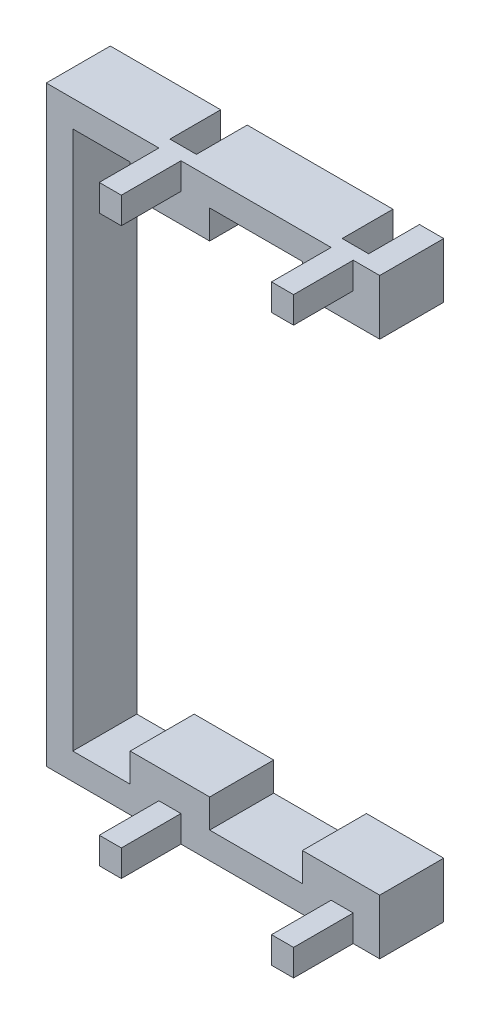
SolidWorks part; units mm, degrees
ref_plane "Front Plane" through (0, 0, 0) normal (0, 0, 1) x (1, 0, 0)
ref_plane "Top Plane" through (0, 0, 0) normal (0, 1, 0) x (1, 0, 0)
ref_plane "Right Plane" through (0, 0, 0) normal (1, 0, 0) x (0, 0, -1)
sketch "Sketch1" plane through (0, 0, 0) normal (0, 0, 1) x (1, 0, 0)
  line L0 (53.75, -8.25) -> (30.5, -8.25) construction
  line L1 (-4.25, 58.75) -> (8.25, 58.75)
  line L2 (-4.25, 58.75) -> (-4.25, -8.25)
  line L3 (-4.25, -8.25) -> (8.25, -8.25)
  line L4 (33.5, 58.75) -> (33.5, 52.5)
  line L5 (30.5, -5.25) -> (30.5, -8.25) construction
  line L6 (-1.25, 55.75) -> (5.25, 55.75)
  line L7 (-1.25, 55.75) -> (-1.25, -5.25)
  line L8 (-1.25, -5.25) -> (5.25, -5.25)
  line L9 (14.25, 55.75) -> (24.75, 55.75)
  line L10 (14.25, -5.25) -> (24.75, -5.25)
  line L11 (14.25, -8.25) -> (14.25, -2) construction
  line L12 (24.75, 52.5) -> (33.75, 52.5) construction
  line L13 (5.25, 55.75) -> (5.25, 52.5)
  line L14 (11.25, -8.5) -> (11.25, -5)
  line L15 (11.25, -5) -> (8.25, -5)
  line L16 (8.25, -5) -> (8.25, -8.5)
  line L17 (8.25, -8.5) -> (11.25, -8.5)
  line L18 (11.25, -8.25) -> (11.25, -5)
  line L19 (11.25, -5) -> (8.25, -5)
  line L20 (8.25, -5) -> (8.25, -8.25)
  line L21 (11.25, 58.75) -> (27.75, 58.75)
  line L22 (5.25, 52.5) -> (14.25, 52.5)
  line L23 (14.25, 52.5) -> (14.25, 55.75)
  line L24 (24.75, 55.75) -> (24.75, 52.5)
  line L25 (24.75, 52.5) -> (33.5, 52.5)
  line L26 (27.75, -8.5) -> (30.75, -8.5)
  line L27 (30.75, -8.5) -> (30.75, -5)
  line L28 (30.75, -5) -> (27.75, -5)
  line L29 (27.75, -5) -> (27.75, -8.5)
  line L30 (30.75, 58.75) -> (33.5, 58.75)
  line L31 (30.75, -8.25) -> (30.75, -5)
  line L32 (30.75, -5) -> (27.75, -5)
  line L33 (27.75, -5) -> (27.75, -8.25)
  line L34 (33.5, -2) -> (33.5, -8.25)
  line L35 (11.25, -5.25) -> (27.75, -5.25) construction
  line L36 (33.5, -2) -> (24.75, -2)
  line L37 (24.75, -2) -> (24.75, -5.25)
  line L38 (11.25, 59) -> (8.25, 59)
  line L39 (8.25, 59) -> (8.25, 55.5)
  line L40 (8.25, 55.5) -> (11.25, 55.5)
  line L41 (11.25, 55.5) -> (11.25, 59)
  line L42 (30.75, -8.25) -> (33.5, -8.25)
  line L43 (8.25, 58.75) -> (8.25, 55.5)
  line L44 (8.25, 55.5) -> (11.25, 55.5)
  line L45 (11.25, 55.5) -> (11.25, 58.75)
  line L46 (11.25, -8.25) -> (27.75, -8.25)
  line L47 (14.25, -5.25) -> (14.25, -2)
  line L48 (14.25, -2) -> (5.25, -2)
  line L49 (5.25, -2) -> (5.25, -5.25)
  line L50 (27.75, 59) -> (27.75, 55.5)
  line L51 (27.75, 55.5) -> (30.75, 55.5)
  line L52 (30.75, 55.5) -> (30.75, 59)
  line L53 (30.75, 59) -> (27.75, 59)
  line L54 (27.75, 58.75) -> (27.75, 55.5)
  line L55 (27.75, 55.5) -> (30.75, 55.5)
  line L56 (30.75, 55.5) -> (30.75, 58.75)
  line L57 (-1.25, 55.75) -> (8.25, 55.75) construction
  line L58 (5.25, 58.75) -> (5.25, 52.5) construction
  line L59 (11.25, 55.75) -> (27.75, 55.75) construction
  line L60 (14.25, 52.5) -> (14.25, 58.75) construction
  line L61 (33.75, -2) -> (24.75, -2) construction
  line L62 (24.75, 58.75) -> (24.75, 52.5) construction
  line L63 (33.75, 52.5) -> (33.75, 58.75) construction
  line L64 (33.75, -8.25) -> (33.75, -2) construction
  line L65 (24.75, -2) -> (24.75, -8.25) construction
  line L66 (-1.25, -5.25) -> (8.25, -5.25) construction
  line L67 (5.25, -2) -> (5.25, -8.25) construction
  dimension "D1" = 3
  dimension "D2" = 0.25
  dimension "D3" = 0.25
  dimension "D4" = 0.25
  dimension "D5" = 0.25
  dimension "D6" = 3
  dimension "D7" = 3
  dimension "D8" = 3
  dimension "D9" = 3
  dimension "D10" = 3
  dimension "D12" = 3
  dimension "D13" = 3
extrude "Boss-Extrude1" add sketch "Sketch1" along normal offset from surface (104.6107 mm away) 1.5
sketch "Sketch2" plane through (0, 0, 5.75) normal (0, 0, 1) x (1, 0, 0)
  line L3 (11, -8.25) -> (11, -5.25) construction
  line L4 (11, -5.25) -> (8.5, -5.25) construction
  line L5 (8.5, -5.25) -> (8.5, -8.25) construction
  line L15 (8.5, -8.25) -> (11, -8.25) construction
  line L16 (28, -8.25) -> (30.5, -8.25) construction
  line L17 (30.5, -8.25) -> (30.5, -5.25) construction
  line L18 (30.5, -5.25) -> (28, -5.25) construction
  line L19 (28, -5.25) -> (28, -8.25) construction
  line L20 (28, 58.75) -> (28, 55.75) construction
  line L21 (28, 55.75) -> (30.5, 55.75) construction
  line L22 (30.5, 55.75) -> (30.5, 58.75) construction
  line L23 (30.5, 58.75) -> (28, 58.75) construction
  line L24 (11, 58.75) -> (8.5, 58.75) construction
  line L25 (8.5, 58.75) -> (8.5, 55.75) construction
  line L26 (8.5, 55.75) -> (11, 55.75) construction
  line L27 (11, 55.75) -> (11, 58.75) construction
  line L28 (11, -8.25) -> (11, -5.25)
  line L29 (11, -5.25) -> (8.5, -5.25)
  line L30 (8.5, -5.25) -> (8.5, -8.25)
  line L31 (8.5, -8.25) -> (11, -8.25)
  line L32 (28, -8.25) -> (30.5, -8.25)
  line L33 (30.5, -8.25) -> (30.5, -5.25)
  line L34 (30.5, -5.25) -> (28, -5.25)
  line L35 (28, -5.25) -> (28, -8.25)
  line L36 (28, 58.75) -> (28, 55.75)
  line L37 (28, 55.75) -> (30.5, 55.75)
  line L38 (30.5, 55.75) -> (30.5, 58.75)
  line L39 (30.5, 58.75) -> (28, 58.75)
  line L40 (11, 58.75) -> (8.5, 58.75)
  line L41 (8.5, 58.75) -> (8.5, 55.75)
  line L42 (8.5, 55.75) -> (11, 55.75)
  line L43 (11, 55.75) -> (11, 58.75)
extrude "Boss-Extrude2" add sketch "Sketch2" along normal up to surface (8.25 mm away)
sketch "Sketch3" plane through (0, 0, 5.75) normal (0, 0, -1) x (-1, 0, 0)
  line L0 (-11, 58.75) -> (-8.5, 58.75) construction
  line L1 (-11.25, 58.75) -> (-8.25, 58.75)
  line L2 (-28, 58.75) -> (-30.5, 58.75) construction
  line L3 (-28, -8.25) -> (-30.5, -8.25) construction
  line L4 (-8.5, -8.25) -> (-11, -8.25) construction
  line L5 (-27.75, 58.75) -> (-30.75, 58.75)
  line L6 (-27.75, -8.25) -> (-30.75, -8.25)
  line L7 (-8.25, -8.25) -> (-11.25, -8.25)
  line L8 (-11.25, -8.5) -> (-8.25, -8.5)
  line L9 (-8.25, -8.5) -> (-8.25, -5)
  line L10 (-8.25, -5) -> (-11.25, -5)
  line L11 (-11.25, -5) -> (-11.25, -8.5)
  line L13 (-8.25, -8.25) -> (-8.25, -5)
  line L14 (-8.25, -5) -> (-11.25, -5)
  line L15 (-11.25, -5) -> (-11.25, -8.25)
  line L20 (-27.75, -8.5) -> (-27.75, -5)
  line L21 (-27.75, -5) -> (-30.75, -5)
  line L22 (-30.75, -5) -> (-30.75, -8.5)
  line L23 (-30.75, -8.5) -> (-27.75, -8.5)
  line L24 (-27.75, -8.25) -> (-27.75, -5)
  line L25 (-27.75, -5) -> (-30.75, -5)
  line L26 (-30.75, -5) -> (-30.75, -8.25)
  line L32 (-27.75, 59) -> (-30.75, 59)
  line L33 (-30.75, 59) -> (-30.75, 55.5)
  line L34 (-30.75, 55.5) -> (-27.75, 55.5)
  line L35 (-27.75, 55.5) -> (-27.75, 59)
  line L37 (-30.75, 58.75) -> (-30.75, 55.5)
  line L38 (-30.75, 55.5) -> (-27.75, 55.5)
  line L39 (-27.75, 55.5) -> (-27.75, 58.75)
  line L44 (-11.25, 59) -> (-11.25, 55.5)
  line L45 (-11.25, 55.5) -> (-8.25, 55.5)
  line L46 (-8.25, 55.5) -> (-8.25, 59)
  line L47 (-8.25, 59) -> (-11.25, 59)
  line L48 (-11.25, 58.75) -> (-11.25, 55.5)
  line L49 (-11.25, 55.5) -> (-8.25, 55.5)
  line L50 (-8.25, 55.5) -> (-8.25, 58.75)
  point P4 (-30.75, 58.75)
  point P11 (-30.75, -8.25)
  point P22 (-30.75, -8.5)
  point P23 (-11.25, -8.25)
  point P24 (-27.75, -8.25)
  point P25 (-11.3083, 58.75)
  point P26 (-8.25, -8.25)
  point P27 (-27.75, 58.75)
  point P29 (-27.75, 58.7799)
  point P32 (-30.7235, 58.75)
  point P36 (-30.7112, -8.25)
  point P39 (-27.8012, -8.25)
  point P42 (-11.0964, -8.25)
  point P45 (-8.2697, -8.25)
  dimension "D1" = 0.25
  dimension "D2" = 0.25
  dimension "D3" = 0.25
  dimension "D4" = 0.25
extrude "Boss-Extrude3" add sketch "Sketch3" against normal up to surface (1.5 mm away) up to face at (17, 25.25, 7.25)
